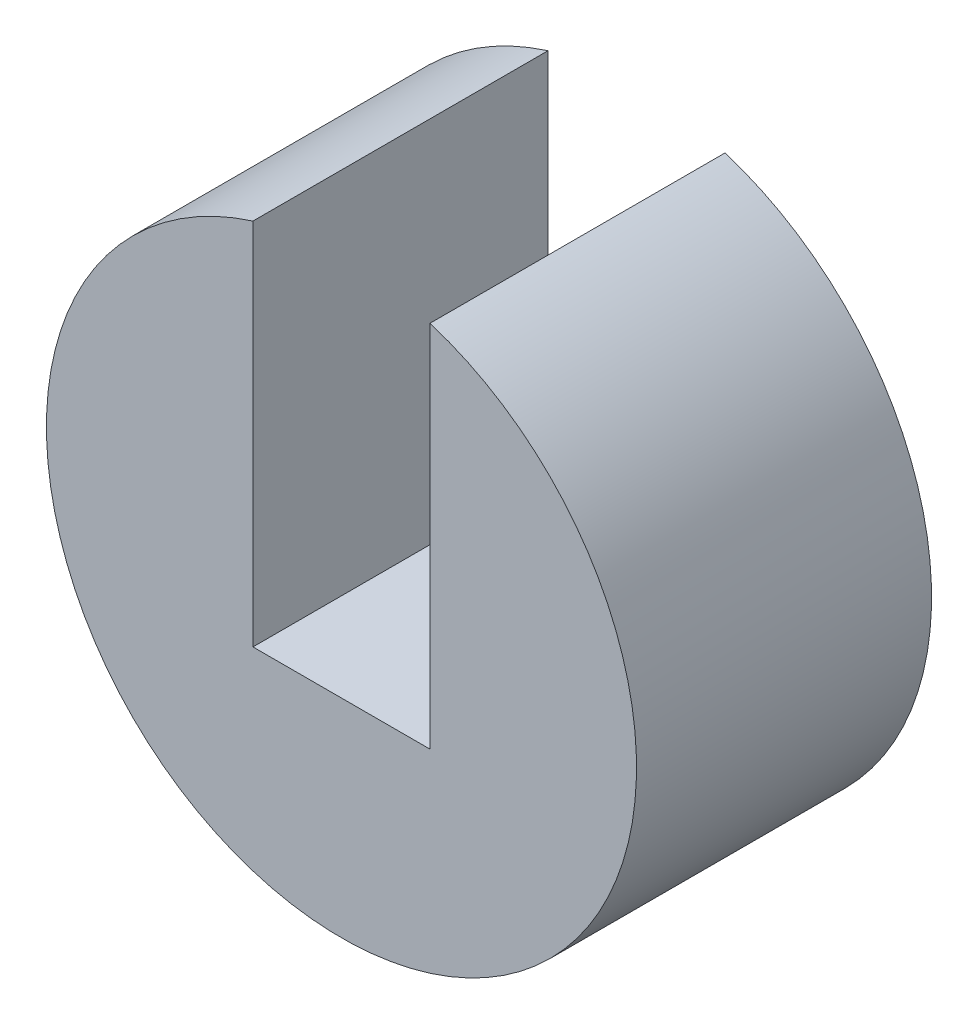
SolidWorks part; units mm, degrees
ref_plane "Front Plane" through (0, 0, 0) normal (0, 0, 1) x (1, 0, 0)
ref_plane "Top Plane" through (0, 0, 0) normal (0, 1, 0) x (1, 0, 0)
ref_plane "Right Plane" through (0, 0, 0) normal (1, 0, 0) x (0, 0, -1)
sketch "Sketch1" plane through (0, 0, 0) normal (0, 0, 1) x (1, 0, 0)
  line L1 (1.5, 3.125) -> (-1.5, 3.125)
  line L2 (1.5, 3.125) -> (1.5, -3.125)
  line L3 (1.5, -3.125) -> (-1.5, -3.125)
  line L4 (-1.5, 3.125) -> (-1.5, -3.125)
  line L5 (1.5, 3.125) -> (-1.5, -3.125) construction
  line L6 (1.5, -3.125) -> (-1.5, 3.125) construction
  circle A0 centre (0, -1.6447) radius 5
  point P0 (0, 0)
  dimension "D3" = 10
  dimension "D1" = 3
  dimension "D2" = 6.25
extrude "Boss-Extrude1" add sketch "Sketch1" along normal blind 5 contours L4 A0 L2 L3
